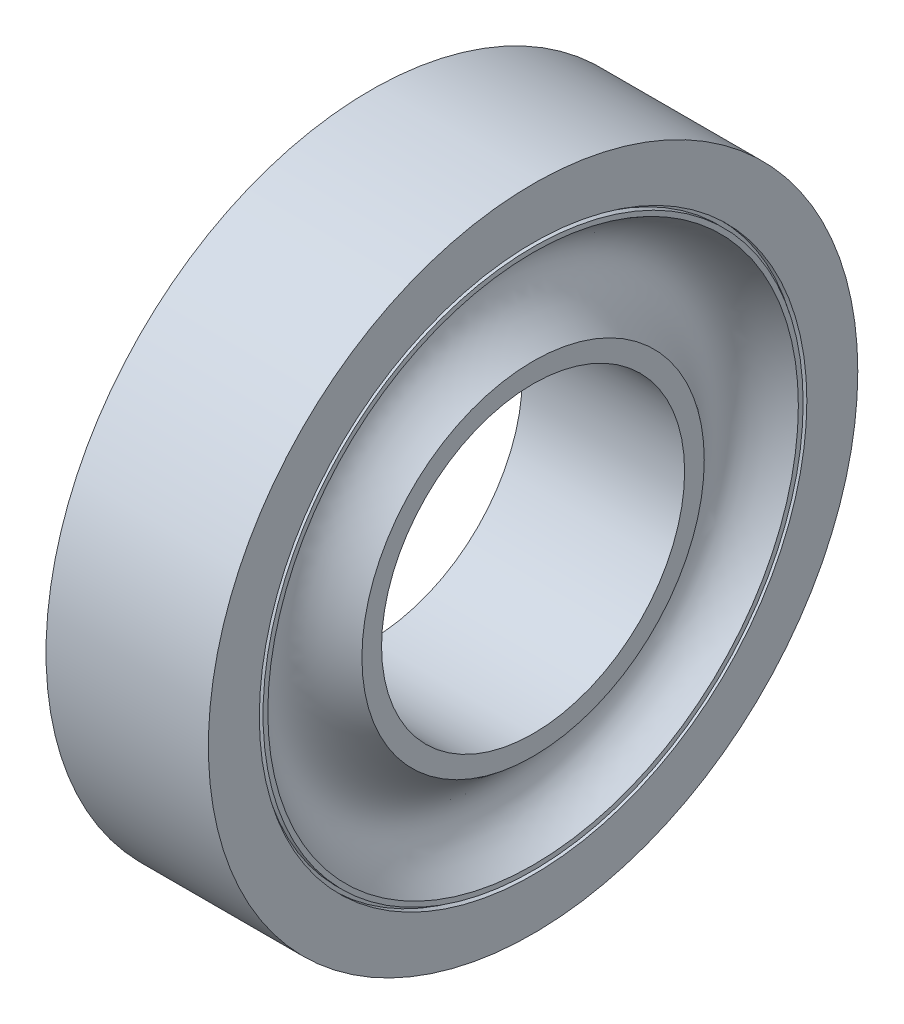
SolidWorks part; units mm, degrees
ref_plane "Front Plane" through (0, 0, 0) normal (0, 0, 1) x (1, 0, 0)
ref_plane "Top Plane" through (0, 0, 0) normal (0, 1, 0) x (1, 0, 0)
ref_plane "Right Plane" through (0, 0, 0) normal (1, 0, 0) x (0, 0, -1)
sketch "Sketch1" plane through (0, 0, 0) normal (0, 0, 1) x (1, 0, 0)
  line L0 (37.4228, 0) -> (-48.477, 0) construction
  line L1 (0, 55.955) -> (0, -45.0267) construction
  line L2 (7.5, 14) -> (-7.5, 14)
  line L3 (-7.5, 14) -> (-7.5, 15.815)
  line L4 (-7.5, 24.5077) -> (-7.5, 24.9503)
  line L5 (-7.5, 24.9503) -> (-6.9581, 24.9503)
  line L6 (-6.9581, 24.9503) -> (-6.9581, 25.2929)
  line L7 (-6.9581, 25.2929) -> (-7.5, 25.2929)
  line L8 (-7.5, 25.2929) -> (-7.5, 30)
  line L9 (-7.5, 30) -> (7.5, 30)
  line L10 (7.5, 25.2929) -> (7.5, 30)
  line L11 (6.9581, 25.2929) -> (7.5, 25.2929)
  line L12 (6.9581, 24.9503) -> (6.9581, 25.2929)
  line L13 (7.5, 24.9503) -> (6.9581, 24.9503)
  line L14 (7.5, 24.5077) -> (7.5, 24.9503)
  line L15 (7.5, 14) -> (7.5, 15.815)
  spline S0 degree 2 poles (-7.5, 15.815) (-0.2215, 20.8548) (-7.5, 24.5077) knots 0 0 0 1 1 1
  spline S1 degree 2 poles (7.5, 15.815) (0.2215, 20.8548) (7.5, 24.5077) knots 0 0 0 1 1 1
  point P5 (-7.5, 27.6465)
  point P25 (0, 30)
  point P30 (0, 14)
  dimension "D1" = 28
  dimension "D2" = 60
  dimension "D3" = 15
revolve "Revolve1" add sketch "Sketch1" angle 360 about L0
